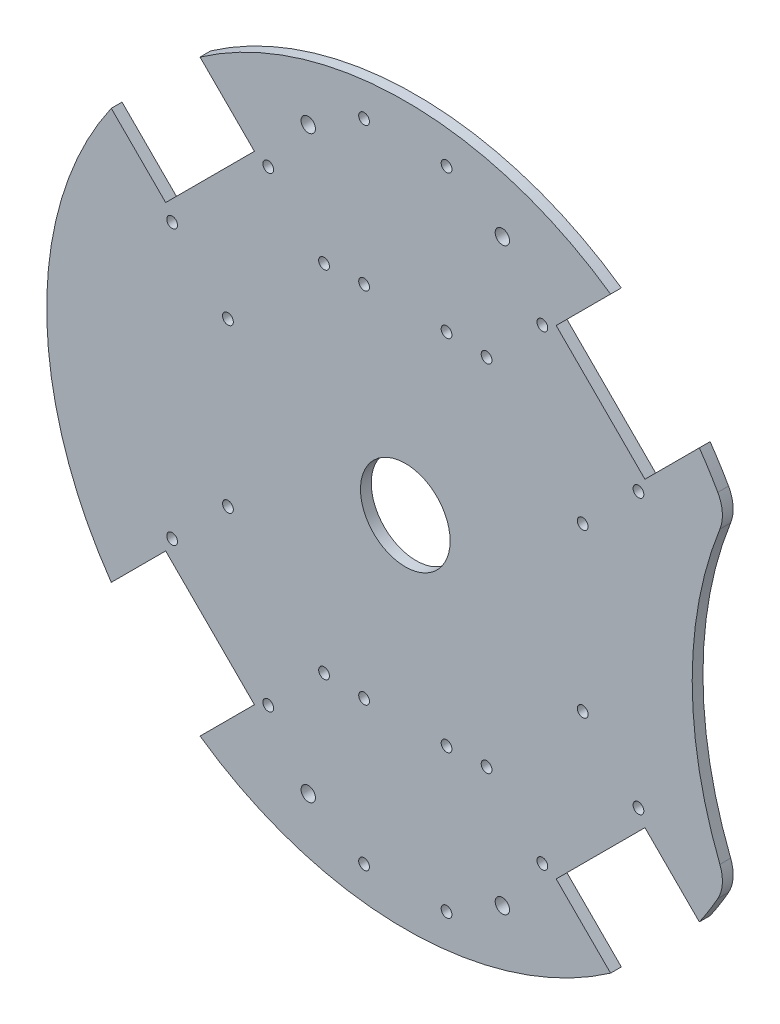
SolidWorks part; units mm, degrees
ref_plane "Alzado" through (0, 0, 0) normal (0, 0, 1) x (1, 0, 0)
ref_plane "Planta" through (0, 0, 0) normal (0, 1, 0) x (1, 0, 0)
ref_plane "Vista lateral" through (0, 0, 0) normal (1, 0, 0) x (0, 0, -1)
sketch "Croquis1" plane through (0, 0, 0) normal (0, 0, 1) x (1, 0, 0)
  circle A0 centre (0, 0) radius 100
  dimension "D1" = 200
extrude "Saliente-Extruir1" add sketch "Croquis1" along normal blind 3
sketch "Croquis3" plane through (0, 0, 3) normal (0, 0, 1) x (1, 0, 0)
  line L0 (0, 0) -> (190, 0) construction
  circle A0 centre (190, 0) radius 110
  dimension "D1" = 220
  dimension "D2" = 190
extrude "Cortar-Extruir1" cut sketch "Croquis3" against normal blind 3
fillet "Redondeo1" radius 10 2 edges at (89.4737, -44.6594, 1.5) (89.4737, 44.6594, 1.5)
sketch "Croquis4" plane through (0, 0, 3) normal (0, 0, 1) x (1, 0, 0)
  line L0 (-100, 0) -> (80, 0) construction
  line L1 (0, 0) -> (0, -100) construction
  line L2 (-54.4472, -54.4472) -> (-51.6188, -51.6188) construction
  line L3 (-58.3363, -83.085) -> (-83.085, -58.3363)
  line L4 (-66.8216, 42.0729) -> (-42.0729, 66.8216)
  line L5 (-83.085, -58.3363) -> (-66.8216, -42.0729)
  line L6 (-58.3363, -83.085) -> (-42.0729, -66.8216)
  line L7 (-42.0729, -66.8216) -> (-66.8216, -42.0729)
  line L8 (-58.3363, 83.085) -> (-42.0729, 66.8216)
  line L9 (-83.085, 58.3363) -> (-58.3363, 83.085)
  line L10 (-83.085, 58.3363) -> (-66.8216, 42.0729)
  line L11 (42.0729, 66.8216) -> (66.8216, 42.0729)
  line L12 (83.085, 58.3363) -> (66.8216, 42.0729)
  line L13 (58.3363, 83.085) -> (83.085, 58.3363)
  line L14 (58.3363, 83.085) -> (42.0729, 66.8216)
  line L15 (66.8216, -42.0729) -> (42.0729, -66.8216)
  line L16 (58.3363, -83.085) -> (42.0729, -66.8216)
  line L17 (83.085, -58.3363) -> (58.3363, -83.085)
  line L18 (83.085, -58.3363) -> (66.8216, -42.0729)
  arc A0 (87.1345, 49.0671) -> (87.1345, -49.0671) centre (0, 0) ccw construction
  arc A1 (87.7193, 40.4803) -> (87.7193, -40.4803) centre (190, 0) ccw construction
  circle A2 centre (-65.0185, -38.2191) radius 1.5
  circle A3 centre (-49.4621, -22.6628) radius 1.5
  circle A4 centre (-22.6628, -49.4621) radius 1.5
  circle A5 centre (-38.2191, -65.0185) radius 1.5
  circle A6 centre (-22.6628, 49.4621) radius 1.5
  circle A7 centre (-38.2191, 65.0185) radius 1.5
  circle A8 centre (-49.4621, 22.6628) radius 1.5
  circle A9 centre (-65.0185, 38.2191) radius 1.5
  circle A10 centre (49.4621, 22.6628) radius 1.5
  circle A11 centre (65.0185, 38.2191) radius 1.5
  circle A12 centre (22.6628, 49.4621) radius 1.5
  circle A13 centre (38.2191, 65.0185) radius 1.5
  circle A14 centre (22.6628, -49.4621) radius 1.5
  circle A15 centre (38.2191, -65.0185) radius 1.5
  circle A16 centre (49.4621, -22.6628) radius 1.5
  circle A17 centre (65.0185, -38.2191) radius 1.5
  circle A18 centre (0, 0) radius 12.5
  point P64 (0, 0)
  dimension "D5" = 3
  dimension "D6" = 3
  dimension "D7" = 3
  dimension "D8" = 22
  dimension "D9" = 3
  dimension "D10" = 37.9
  dimension "D11" = 22
  dimension "D12" = 37.9
  dimension "D14" = 54.4068
  dimension "D17" = 25
  dimension "D1" = 35
  dimension "D2" = 23
  dimension "D3" = 23
  dimension "D4" = 17.5
  dimension "D13" = 4
  dimension "D15" = 77
  dimension "D16" = 4
extrude "Cortar-Extruir2" cut sketch "Croquis4" against normal through all
sketch "Croquis5" plane through (0, 0, 0) normal (0, 0, -1) x (-1, 0, 0)
  line L0 (0, -100) -> (0, -90) construction
  line L1 (11.5, -90) -> (-11.5, -90) construction
  line L3 (-11.5, -90) -> (-11.5, -50) construction
  line L4 (0, 0) -> (0, -100) construction
  line L5 (-11.5, -50) -> (11.5, -50) construction
  line L6 (11.5, -50) -> (11.5, -90) construction
  circle A0 centre (11.5, -90) radius 1.5
  circle A1 centre (-11.5, -90) radius 1.5
  circle A2 centre (-11.5, -50) radius 1.5
  circle A3 centre (11.5, -50) radius 1.5
  arc A5 (-57.2451, -81.9939) -> (57.2451, -81.9939) centre (0, 0) ccw construction
  circle A9 centre (-11.5, 90) radius 1.5
  circle A10 centre (11.5, 90) radius 1.5
  circle A11 centre (11.5, 50) radius 1.5
  circle A12 centre (-11.5, 50) radius 1.5
  circle A25 centre (90, 11.5) radius 1.5 [skipped]
  circle A26 centre (90, -11.5) radius 1.5 [skipped]
  circle A27 centre (50, 11.5) radius 1.5 [skipped]
  circle A28 centre (50, -11.5) radius 1.5 [skipped]
  circle A29 centre (-90, -11.5) radius 1.5 [skipped]
  circle A30 centre (-90, 11.5) radius 1.5 [skipped]
  circle A31 centre (-50, 11.5) radius 1.5 [skipped]
  circle A32 centre (-50, -11.5) radius 1.5 [skipped]
  point P41 (0, 0)
  point P59 (0, 0)
  dimension "D1" = 23
  dimension "D3" = 3
  dimension "D4" = 3
  dimension "D5" = 3
  dimension "D6" = 3
  dimension "D2" = 40
  dimension "D7" = 4
extrude "Cortar-Extruir3" cut sketch "Croquis5" against normal through all
sketch "Croquis7" plane through (0, 0, 0) normal (0, 0, -1) x (-1, 0, 0)
  line L0 (0, 0) -> (0, -87.26) construction
  line L1 (33.54, -87.26) -> (-33.54, -87.26) construction
  line L2 (33.54, -87.26) -> (33.54, -74.31) construction
  line L3 (33.54, -74.31) -> (20.59, -74.31) construction
  line L4 (-33.54, -87.26) -> (-33.54, -74.31) construction
  line L5 (-33.54, -74.31) -> (-20.59, -74.31) construction
  line L6 (-20.59, -74.31) -> (-33.54, -87.26) construction
  line L7 (20.59, -74.31) -> (33.54, -87.26) construction
  line L10 (-12.5, 0) -> (12.5, 0) construction
  circle A0 centre (-27.065, -80.785) radius 2
  circle A1 centre (27.065, -80.785) radius 2
  arc A2 (-57.2451, -81.9939) -> (57.2451, -81.9939) centre (0, 0) ccw construction
  circle A3 centre (0, 0) radius 12.5 construction
  circle A4 centre (27.065, 80.785) radius 2
  circle A5 centre (-27.065, 80.785) radius 2
  dimension "D1" = 4
  dimension "D2" = 4
  dimension "D6" = 6.475
  dimension "D7" = 6.475
  dimension "D3" = 87.26
  dimension "D4" = 18.3141
  dimension "D5" = 18.3141
  dimension "D8" = 67.08
extrude "Cortar-Extruir5" cut sketch "Croquis7" against normal blind 10
